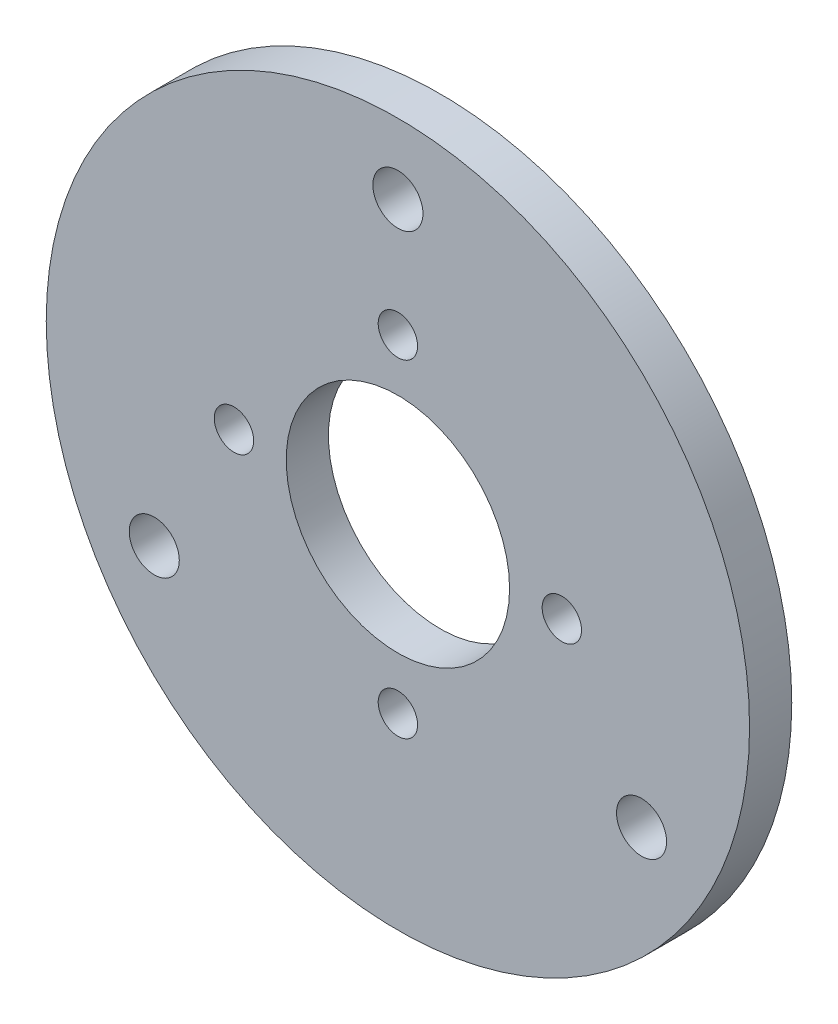
SolidWorks part; units mm, degrees
material "Cast Alloy Steel"
ref_plane "Front Plane" through (0, 0, 0) normal (0, 0, 1) x (1, 0, 0)
ref_plane "Top Plane" through (0, 0, 0) normal (0, 1, 0) x (1, 0, 0)
ref_plane "Right Plane" through (0, 0, 0) normal (1, 0, 0) x (0, 0, -1)
sketch "Sketch1" plane through (0, 0, 0) normal (0, 0, 1) x (1, 0, 0)
  circle A0 centre (0, 0) radius 15.875
  circle A1 centre (0, 0) radius 3.9688
  dimension "D1" = 7.9375
  dimension "D2" = 31.75
extrude "Boss-Extrude1" add sketch "Sketch1" along normal blind 1.905
hole_wizard "X (0.397) Diameter Hole1" positions "Sketch3" profile "Sketch2" hole size "X" standard "ANSI Inch"
sketch "Sketch3" plane through (0, 0, 1.905) normal (0, 0, 1) x (1, 0, 0)
  point P0 (0, 0)
sketch "Sketch2" plane through (0, 0, 1.905) normal (1, 0, 0) x (0, -1, 0)
  line L0 (0, 0) -> (0, 15.7295)
  line L1 (0, 15.7295) -> (5.0419, 12.7)
  line L2 (5.0419, 12.7) -> (5.0419, 0)
  line L5 (5.0419, 0) -> (0, 0)
  line L10 (0, 15.7295) -> (-5.0419, 12.7) construction
  line L11 (0, -6.35) -> (0, 107.95) construction
  dimension "Hole Dia." = 10.0838
  dimension "Hole Depth" = 12.7
  dimension "Drill Angle" = 118
hole_wizard "#4-40 Tapped Hole1" positions "Sketch5" profile "Sketch4" tap size "#4-40" standard "ANSI Inch"
sketch "Sketch5" plane through (0, 0, 1.905) normal (0, 0, 1) x (1, 0, 0)
  point P0 (0, 12.7)
  dimension "D1" = 12.7
sketch "Sketch4" plane through (0, 12.7, 1.905) normal (1, 0, 0) x (0, -1, 0)
  line L0 (0, 0) -> (0, 9.5438)
  line L1 (0, 9.5438) -> (1.1303, 8.8646)
  line L2 (1.1303, 8.8646) -> (1.1303, 0)
  line L5 (1.1303, 0) -> (0, 0)
  line L10 (0, 9.5438) -> (-1.1303, 8.8646) construction
  line L11 (0, -6.35) -> (0, 107.95) construction
  dimension "Tap Drill Dia." = 2.2606
  dimension "Tap Drill Depth" = 8.8646
  dimension "Drill Angle" = 118
pattern_circular "CirPattern1" count 3 over 360 about axis through (0, 0, 0) along (0, 0, 1) of "#4-40 Tapped Hole1"
hole_wizard "#2-56 Tapped Hole1" positions "Sketch7" profile "Sketch6" tap size "#2-56" standard "ANSI Inch"
sketch "Sketch7" plane through (0, 0, 1.905) normal (0, 0, 1) x (1, 0, 0)
  point P0 (0, 7.4)
  dimension "D1" = 7.4
sketch "Sketch6" plane through (0, 7.4, 1.905) normal (1, 0, 0) x (0, -1, 0)
  line L0 (0, 0) -> (0, 7.189)
  line L1 (0, 7.189) -> (0.889, 6.6548)
  line L2 (0.889, 6.6548) -> (0.889, 0)
  line L5 (0.889, 0) -> (0, 0)
  line L10 (0, 7.189) -> (-0.889, 6.6548) construction
  line L11 (0, -6.35) -> (0, 107.95) construction
  dimension "Tap Drill Dia." = 1.778
  dimension "Tap Drill Depth" = 6.6548
  dimension "Drill Angle" = 118
pattern_circular "CirPattern2" count 4 over 360 about axis through (0, 0, 0) along (0, 0, 1) of "#2-56 Tapped Hole1"
